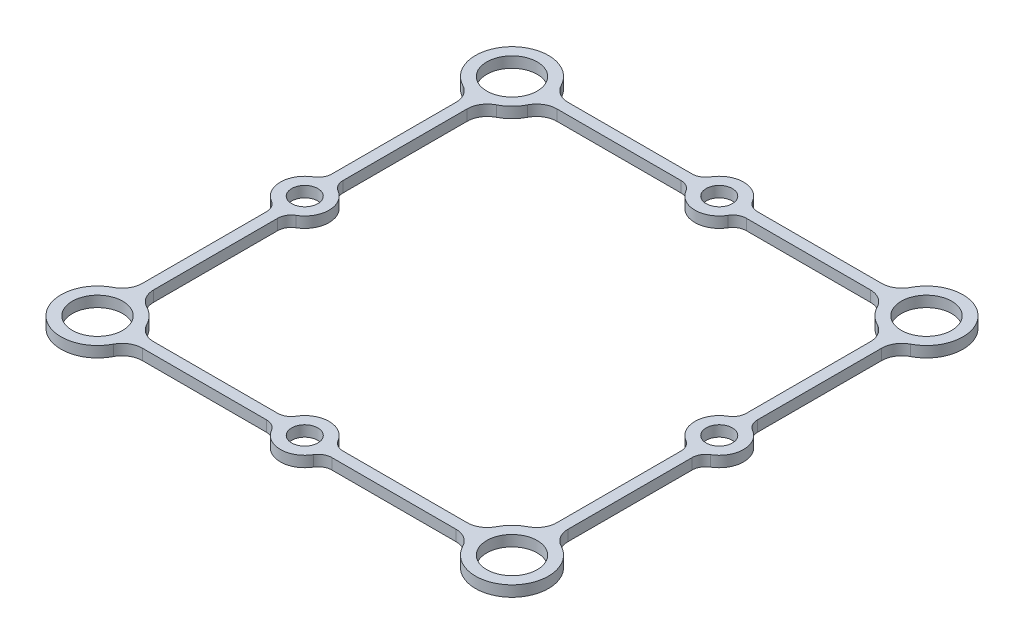
SolidWorks part; units mm, degrees
material "Custom Plastic"
ref_plane "Front Plane" through (0, 0, 0) normal (0, 0, 1) x (1, 0, 0)
ref_plane "Top Plane" through (0, 0, 0) normal (0, 1, 0) x (1, 0, 0)
ref_plane "Right Plane" through (0, 0, 0) normal (1, 0, 0) x (0, 0, -1)
sketch "Sketch1" plane through (0, 0, 0) normal (0, 1, 0) x (1, 0, 0)
  line L0 (0, 0) -> (0, 24.4542) construction
  line L1 (-30.445, -30.445) -> (30.445, -30.445) construction
  line L2 (-30.445, -30.445) -> (-30.445, 30.445) construction
  line L3 (-30.445, 30.445) -> (30.445, 30.445) construction
  line L4 (30.445, -30.445) -> (30.445, 30.445) construction
  line L5 (-30.445, -30.445) -> (30.445, 30.445) construction
  line L6 (-30.445, 30.445) -> (30.445, -30.445) construction
  line L7 (-21.3316, 0) -> (0, 0) construction
  line L8 (-25.1489, 31.27) -> (-3.4785, 31.27)
  line L9 (-25.1489, 29.62) -> (-3.4785, 29.62)
  line L10 (25.1489, 31.27) -> (3.4785, 31.27)
  line L11 (25.1489, 29.62) -> (3.4785, 29.62)
  line L12 (31.27, 25.1489) -> (31.27, 3.4785)
  line L13 (29.62, 25.1489) -> (29.62, 3.4785)
  line L14 (31.27, -25.1489) -> (31.27, -3.4785)
  line L15 (29.62, -25.1489) -> (29.62, -3.4785)
  line L16 (25.1489, -29.62) -> (3.4785, -29.62)
  line L17 (25.1489, -31.27) -> (3.4785, -31.27)
  line L18 (-29.62, 25.1489) -> (-29.62, 3.4785)
  line L19 (-31.27, 25.1489) -> (-31.27, 3.4785)
  line L20 (-31.27, -25.1489) -> (-31.27, -3.4785)
  line L21 (-29.62, -25.1489) -> (-29.62, -3.4785)
  line L22 (-25.1489, -31.27) -> (-3.4785, -31.27)
  line L23 (-25.1489, -29.62) -> (-3.4785, -29.62)
  line L24 (-34.155, 30.445) -> (-34.155, 88.2809) construction
  line L25 (34.155, 30.445) -> (34.155, 88.2809) construction
  arc A0 (-29.62, 25.1489) -> (-25.1489, 29.62) centre (-30.445, 30.445) ccw
  circle A1 centre (-30.445, 30.445) radius 3.71
  circle A2 centre (30.445, 30.445) radius 3.71
  arc A3 (25.1489, 31.27) -> (31.27, 25.1489) centre (30.445, 30.445) cw
  arc A4 (29.62, -25.1489) -> (25.1489, -29.62) centre (30.445, -30.445) ccw
  circle A5 centre (30.445, -30.445) radius 3.71
  arc A6 (-25.1489, -31.27) -> (-31.27, -25.1489) centre (-30.445, -30.445) cw
  circle A7 centre (-30.445, -30.445) radius 3.71
  circle A8 centre (0, 30.445) radius 1.925
  arc A9 (-3.4785, 29.62) -> (3.4785, 29.62) centre (0, 30.445) ccw
  arc A10 (-29.62, 3.4785) -> (-29.62, -3.4785) centre (-30.445, 0) cw
  circle A11 centre (-30.445, 0) radius 1.925
  arc A12 (-3.4785, -31.27) -> (3.4785, -31.27) centre (0, -30.445) ccw
  circle A13 centre (0, -30.445) radius 1.925
  arc A14 (31.27, 3.4785) -> (31.27, -3.4785) centre (30.445, 0) cw
  circle A15 centre (30.445, 0) radius 1.925
  arc A16 (-25.1489, 31.27) -> (-31.27, 25.1489) centre (-30.445, 30.445) ccw
  arc A17 (3.4785, 31.27) -> (-3.4785, 31.27) centre (0, 30.445) ccw
  arc A18 (29.62, 25.1489) -> (25.1489, 29.62) centre (30.445, 30.445) cw
  arc A19 (29.62, -3.4785) -> (29.62, 3.4785) centre (30.445, 0) cw
  arc A20 (25.1489, -31.27) -> (31.27, -25.1489) centre (30.445, -30.445) ccw
  arc A21 (3.4785, -29.62) -> (-3.4785, -29.62) centre (0, -30.445) ccw
  arc A22 (-29.62, -25.1489) -> (-25.1489, -29.62) centre (-30.445, -30.445) cw
  arc A23 (-31.27, -3.4785) -> (-31.27, 3.4785) centre (-30.445, 0) cw
  point P0 (0, 0)
  dimension "D1" = 1.65
  dimension "D2" = 1.65
  dimension "D5" = 7.42
  dimension "D6" = 3.85
  dimension "D3" = 0.825
  dimension "D4" = 0.825
  dimension "D7" = 68.31
extrude "Boss-Extrude1" add sketch "Sketch1" along normal blind 1.5875
fillet "Fillet3" radius 3 16 edges at (-25.1489, 0.7937, -31.27) (-25.1489, 0.7937, -29.62) (-29.62, 0.7937, -25.1489) (-31.27, 0.7937, -25.1489) (29.62, 0.7937, -25.1489) (25.1489, 0.7937, -29.62) (25.1489, 0.7937, -31.27) (31.27, 0.7937, -25.1489) (31.27, 0.7937, 25.1489) (25.1489, 0.7937, 31.27) (25.1489, 0.7937, 29.62) (29.62, 0.7937, 25.1489) (-31.27, 0.7937, 25.1489) (-29.62, 0.7937, 25.1489) (-25.1489, 0.7937, 29.62) (-25.1489, 0.7937, 31.27)
fillet "Fillet4" radius 2 16 edges at (-3.4785, 0.7937, -29.62) (3.4785, 0.7937, -29.62) (3.4785, 0.7937, -31.27) (-3.4785, 0.7937, -31.27) (29.62, 0.7937, -3.4785) (31.27, 0.7937, -3.4785) (29.62, 0.7937, 3.4785) (31.27, 0.7937, 3.4785) (3.4785, 0.7937, 31.27) (3.4785, 0.7937, 29.62) (-3.4785, 0.7937, 29.62) (-3.4785, 0.7937, 31.27) (-31.27, 0.7937, -3.4785) (-31.27, 0.7937, 3.4785) (-29.62, 0.7937, 3.4785) (-29.62, 0.7937, -3.4785)
